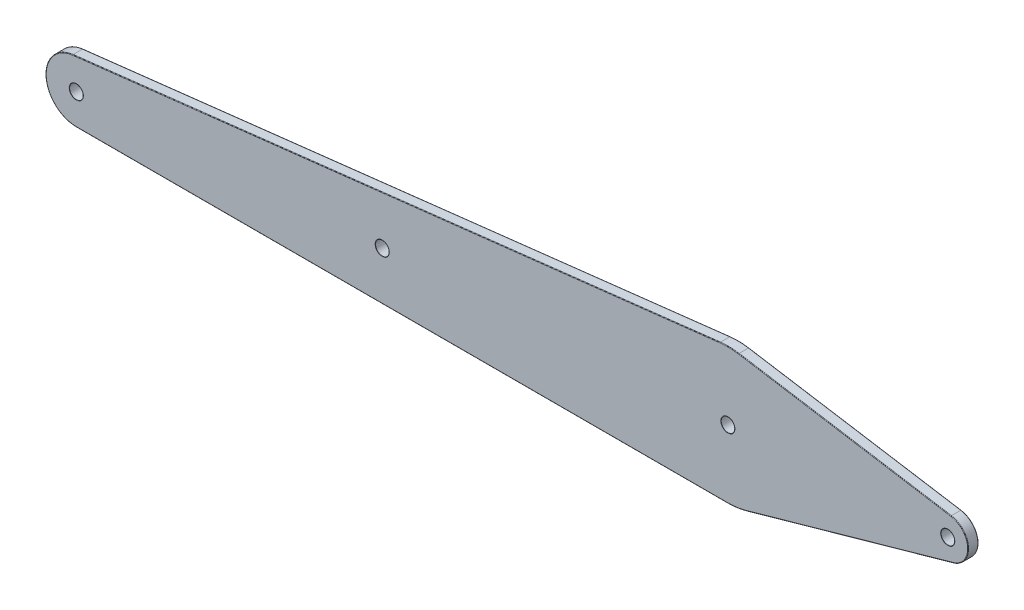
SolidWorks part; units mm, degrees
ref_plane "Front Plane" through (0, 0, 0) normal (0, 0, 1) x (1, 0, 0)
ref_plane "Top Plane" through (0, 0, 0) normal (0, 1, 0) x (1, 0, 0)
ref_plane "Right Plane" through (0, 0, 0) normal (1, 0, 0) x (0, 0, -1)
sketch "Sketch1" plane through (0, 0, 0) normal (0, 0, 1) x (1, 0, 0)
  line L1 (-212.1003, 194.5799) -> (44.2779, 209.2924) construction
  line L2 (-14.983, 186.3319) -> (45.9077, 203.518)
  line L3 (-17.2206, 225.323) -> (45.2364, 215.2153)
  line L4 (-212.1003, 185.5799) -> (-20.4157, 185.5799)
  line L5 (-213.1299, 203.5208) -> (-22.7036, 225.4486)
  circle A0 centre (-212.1003, 194.5799) radius 9 construction
  circle A1 centre (44.2779, 209.2924) radius 6 construction
  circle A2 centre (-20.4157, 205.5799) radius 10 construction
  circle A3 centre (-20.4157, 205.5799) radius 20 construction
  arc A8 (-213.1299, 203.5208) -> (-212.1003, 185.5799) centre (-212.1003, 194.5799) ccw
  arc A12 (-20.4157, 185.5799) -> (-14.983, 186.3319) centre (-20.4157, 205.5799) ccw
  arc A16 (-17.2206, 225.323) -> (-22.7036, 225.4486) centre (-20.4157, 205.5799) ccw
  arc A17 (45.2364, 215.2153) -> (45.9077, 203.518) centre (44.2779, 209.2924) cw
  point P2 (-20.4157, 205.5799)
  point P26 (-122.1003, 199.7446)
  point P27 (-52.1657, -1330.1643)
  dimension "D1" = 18
  dimension "D2" = 40
  dimension "D3" = 20
  dimension "D4" = 12
  dimension "D5" = 64.8
  dimension "D6" = 192
  dimension "D7" = 90
extrude "Boss-Extrude1" add sketch "Sketch1" against normal blind 3
hole_wizard "M3.5 Clearance Hole1" positions "Sketch3" profile "Sketch4" hole size "M3.5" standard "ISO"
sketch "Sketch3" plane through (0, 0, 0) normal (0, 0, 1) x (1, 0, 0)
  point P0 (44.2779, 209.2924)
  point P3 (-20.4157, 205.5799)
  point P6 (-52.1657, -1330.1643)
  point P9 (-122.1003, 199.7446)
  point P12 (-212.1003, 194.5799)
sketch "Sketch4" plane through (44.2779, 209.2924, 0) normal (1, 0, 0) x (0, -1, 0)
  line L0 (0, 0) -> (0, 11.1717)
  line L1 (0, 11.1717) -> (1.95, 10)
  line L2 (1.95, 10) -> (1.95, 0)
  line L5 (1.95, 0) -> (0, 0)
  line L10 (0, 11.1717) -> (-1.95, 10) construction
  line L11 (0, -6.35) -> (0, 107.95) construction
  dimension "Hole Dia." = 3.9
  dimension "Hole Depth" = 10
  dimension "Drill Angle" = 118
fillet "Fillet1" radius 0.15 24 edges at (-221.0856, 194.0642, 0) (-210.1503, 194.5799, 0) (-120.1503, 199.7446, 0) (-18.4657, 205.5799, 0) (46.2279, 209.2924, 0) (-221.0856, 194.0642, -3) (-210.1503, 194.5799, -3) (-120.1503, 199.7446, -3) (-18.4657, 205.5799, -3) (46.2279, 209.2924, -3) (-19.9578, 225.5746, 0) (50.268, 209.6361, 0) (-117.9167, 214.4847, 0) (-117.9167, 214.4847, -3) (50.268, 209.6361, -3) (-19.9578, 225.5746, -3) (-116.258, 185.5799, 0) (14.0079, 220.2692, 0) (15.4623, 194.9249, 0) (-17.6735, 185.7688, 0) (15.4623, 194.9249, -3) (14.0079, 220.2692, -3) (-116.258, 185.5799, -3) (-17.6735, 185.7688, -3)
sketch "草图1" plane through (0, 0, 0) normal (0, 0, 1) x (1, 0, 0)
  circle A0 centre (-20.4157, 205.5799) radius 2
  dimension "D1" = 4
extrude "切除-拉伸1" cut sketch "草图1" against normal blind 10
sketch "草图2" plane through (0, 0, 0) normal (0, 0, 1) x (1, 0, 0)
  circle A0 centre (44.2779, 209.2924) radius 2
  dimension "D1" = 4
extrude "切除-拉伸2" cut sketch "草图2" against normal blind 10
sketch "草图3" plane through (0, 0, 0) normal (0, 0, 1) x (1, 0, 0)
  circle A0 centre (-122.1003, 199.7446) radius 2
  circle A1 centre (-212.1003, 194.5799) radius 2
  dimension "D1" = 4
  dimension "D2" = 4
extrude "切除-拉伸3" cut sketch "草图3" against normal blind 10
